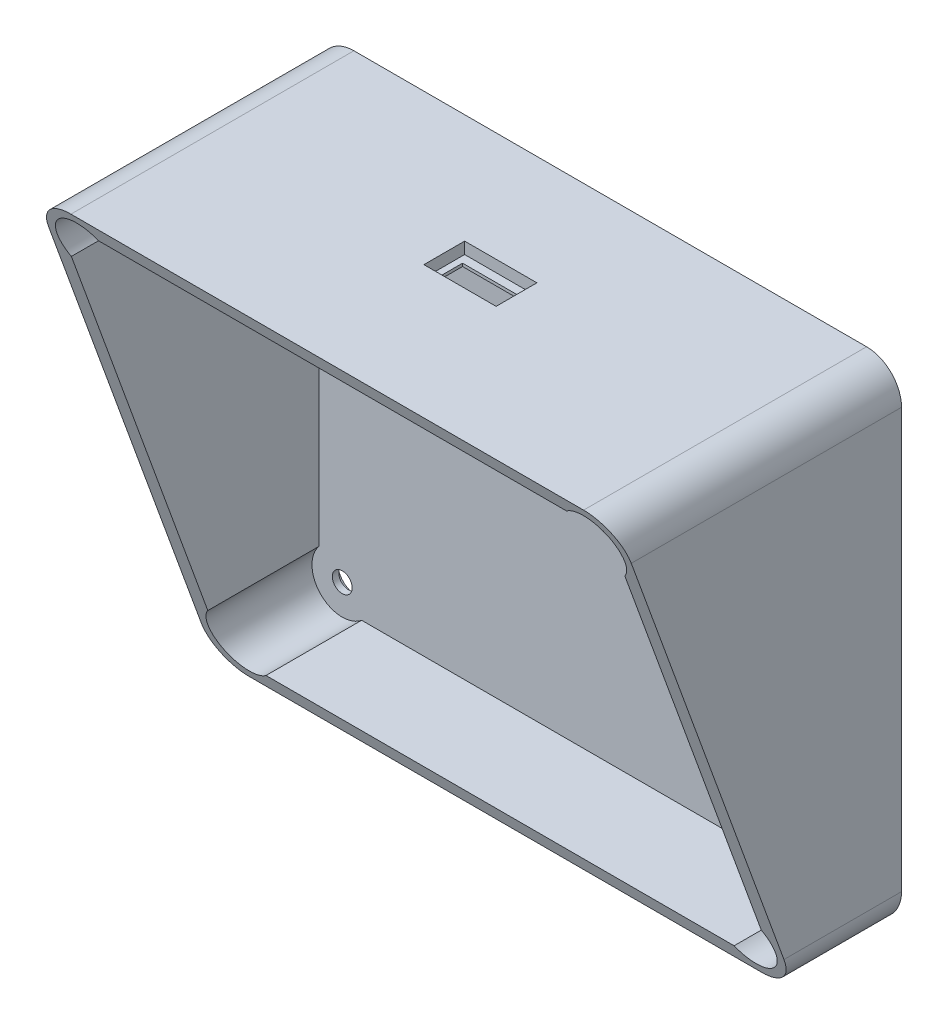
SolidWorks part; units mm, degrees
ref_plane "前视基准面" through (0, 0, 0) normal (0, 0, 1) x (1, 0, 0)
ref_plane "上视基准面" through (0, 0, 0) normal (0, 1, 0) x (1, 0, 0)
ref_plane "右视基准面" through (0, 0, 0) normal (1, 0, 0) x (0, 0, -1)
other "Configuration Table"
sketch "草图1" plane through (0, 0, 0) normal (0, 0, 1) x (1, 0, 0)
  line L0 (6, 0) -> (94, 0)
  line L1 (100, 6) -> (100, 78)
  line L2 (94, 84) -> (6, 84)
  line L3 (0, 78) -> (0, 6)
  arc A0 (94, 0) -> (100, 6) centre (94, 6) ccw
  arc A1 (100, 78) -> (94, 84) centre (94, 78) ccw
  arc A2 (6, 84) -> (0, 78) centre (6, 78) ccw
  arc A3 (0, 6) -> (6, 0) centre (6, 6) ccw
extrude "Outer_R6" add sketch "草图1" along normal blind 55
sketch "草图2" plane through (0, 0, 0) normal (0, 0, 1) x (1, 0, 0)
  line L0 (6, 2.5) -> (94, 2.5)
  line L1 (97.5, 6) -> (97.5, 78)
  line L2 (94, 81.5) -> (6, 81.5)
  line L3 (2.5, 78) -> (2.5, 6)
  arc A0 (94, 2.5) -> (97.5, 6) centre (94, 6) ccw
  arc A1 (97.5, 78) -> (94, 81.5) centre (94, 78) ccw
  arc A2 (6, 81.5) -> (2.5, 78) centre (6, 78) ccw
  arc A3 (2.5, 6) -> (6, 2.5) centre (6, 6) ccw
extrude "Cavity_floor2p5_wall2p5" cut sketch "草图2" along normal blind 65 from offset 2.5
sketch "草图3" plane through (0, 0, 0) normal (1, 0, 0) x (0, 0, -1)
  line L0 (-10.7206, -20) -> (-58.0367, 110)
  line L1 (-58.0367, 110) -> (-120, 110)
  line L2 (-120, 110) -> (-120, -20)
  line L3 (-120, -20) -> (-10.7206, -20)
extrude "Panel_seat_20deg" cut sketch "草图3" against normal through all and the other way through all
sketch "草图4" plane through (0, 0, 0) normal (0, 0, 1) x (1, 0, 0)
  circle A0 centre (6.5, 6.5) radius 5.2
extrude "Internal_post_clearance_0" cut sketch "草图4" along normal blind 60 from offset 2.5
sketch "草图5" plane through (0, 0, 0) normal (0, 0, 1) x (1, 0, 0)
  circle A0 centre (6.5, 6.5) radius 1.7
extrude "Underside_M3_0" cut sketch "草图5" along normal blind 3
sketch "草图6" plane through (0, 0, 0) normal (0, 0, 1) x (1, 0, 0)
  circle A0 centre (6.5, 6.5) radius 3.3
extrude "Underside_head_recess_0" cut sketch "草图6" along normal blind 1.4
sketch "草图7" plane through (0, 0, 0) normal (0, 0, 1) x (1, 0, 0)
  circle A0 centre (93.5, 6.5) radius 5.2
extrude "Internal_post_clearance_1" cut sketch "草图7" along normal blind 60 from offset 2.5
sketch "草图8" plane through (0, 0, 0) normal (0, 0, 1) x (1, 0, 0)
  circle A0 centre (93.5, 6.5) radius 1.7
extrude "Underside_M3_1" cut sketch "草图8" along normal blind 3
sketch "草图9" plane through (0, 0, 0) normal (0, 0, 1) x (1, 0, 0)
  circle A0 centre (93.5, 6.5) radius 3.3
extrude "Underside_head_recess_1" cut sketch "草图9" along normal blind 1.4
sketch "草图10" plane through (0, 0, 0) normal (0, 0, 1) x (1, 0, 0)
  circle A0 centre (6.5, 77.5) radius 5.2
extrude "Internal_post_clearance_2" cut sketch "草图10" along normal blind 60 from offset 2.5
sketch "草图11" plane through (0, 0, 0) normal (0, 0, 1) x (1, 0, 0)
  circle A0 centre (6.5, 77.5) radius 1.7
extrude "Underside_M3_2" cut sketch "草图11" along normal blind 3
sketch "草图12" plane through (0, 0, 0) normal (0, 0, 1) x (1, 0, 0)
  circle A0 centre (6.5, 77.5) radius 3.3
extrude "Underside_head_recess_2" cut sketch "草图12" along normal blind 1.4
sketch "草图13" plane through (0, 0, 0) normal (0, 0, 1) x (1, 0, 0)
  circle A0 centre (93.5, 77.5) radius 5.2
extrude "Internal_post_clearance_3" cut sketch "草图13" along normal blind 60 from offset 2.5
sketch "草图14" plane through (0, 0, 0) normal (0, 0, 1) x (1, 0, 0)
  circle A0 centre (93.5, 77.5) radius 1.7
extrude "Underside_M3_3" cut sketch "草图14" along normal blind 3
sketch "草图15" plane through (0, 0, 0) normal (0, 0, 1) x (1, 0, 0)
  circle A0 centre (93.5, 77.5) radius 3.3
extrude "Underside_head_recess_3" cut sketch "草图15" along normal blind 1.4
sketch "草图16" plane through (0, 0, 0) normal (0, 0, 1) x (1, 0, 0)
  circle A0 centre (37, 49) radius 2.2
  circle A1 centre (63, 49) radius 2.2
  circle A2 centre (37, 78) radius 2.2
  circle A3 centre (63, 78) radius 2.2
extrude "Centered_carrier_supports_Z7" add sketch "草图16" along normal blind 4.5 from offset 2.5
sketch "草图17" plane through (0, 0, 0) normal (0, 0, 1) x (1, 0, 0)
  circle A0 centre (37, 49) radius 1.15
  circle A1 centre (63, 49) radius 1.15
  circle A2 centre (37, 78) radius 1.15
  circle A3 centre (63, 78) radius 1.15
extrude "Carrier_M2_clearance" cut sketch "草图17" along normal blind 8
sketch "草图18" plane through (0, 0, 0) normal (0, 0, 1) x (1, 0, 0)
  circle A0 centre (37, 49) radius 2.2
  circle A1 centre (63, 49) radius 2.2
  circle A2 centre (37, 78) radius 2.2
  circle A3 centre (63, 78) radius 2.2
extrude "Carrier_head_recess" cut sketch "草图18" along normal blind 1.2
sketch "草图19" plane through (0, 0, 0) normal (0, 1, 0) x (1, 0, 0)
  line L0 (44.9, -20.25) -> (55.1, -20.25)
  line L1 (55.1, -20.25) -> (55.1, -24.33)
  line L2 (55.1, -24.33) -> (44.9, -24.33)
  line L3 (44.9, -24.33) -> (44.9, -20.25)
extrude "USB_C_centered_inner_opening" cut sketch "草图19" along normal blind 6 from offset 80
sketch "草图20" plane through (0, 0, 0) normal (0, 1, 0) x (1, 0, 0)
  line L0 (43.8, -18.79) -> (56.2, -18.79)
  line L1 (56.2, -18.79) -> (56.2, -25.79)
  line L2 (56.2, -25.79) -> (43.8, -25.79)
  line L3 (43.8, -25.79) -> (43.8, -18.79)
extrude "USB_plug_shoulder_shallow_recess" cut sketch "草图20" along normal blind 3 from offset 82
